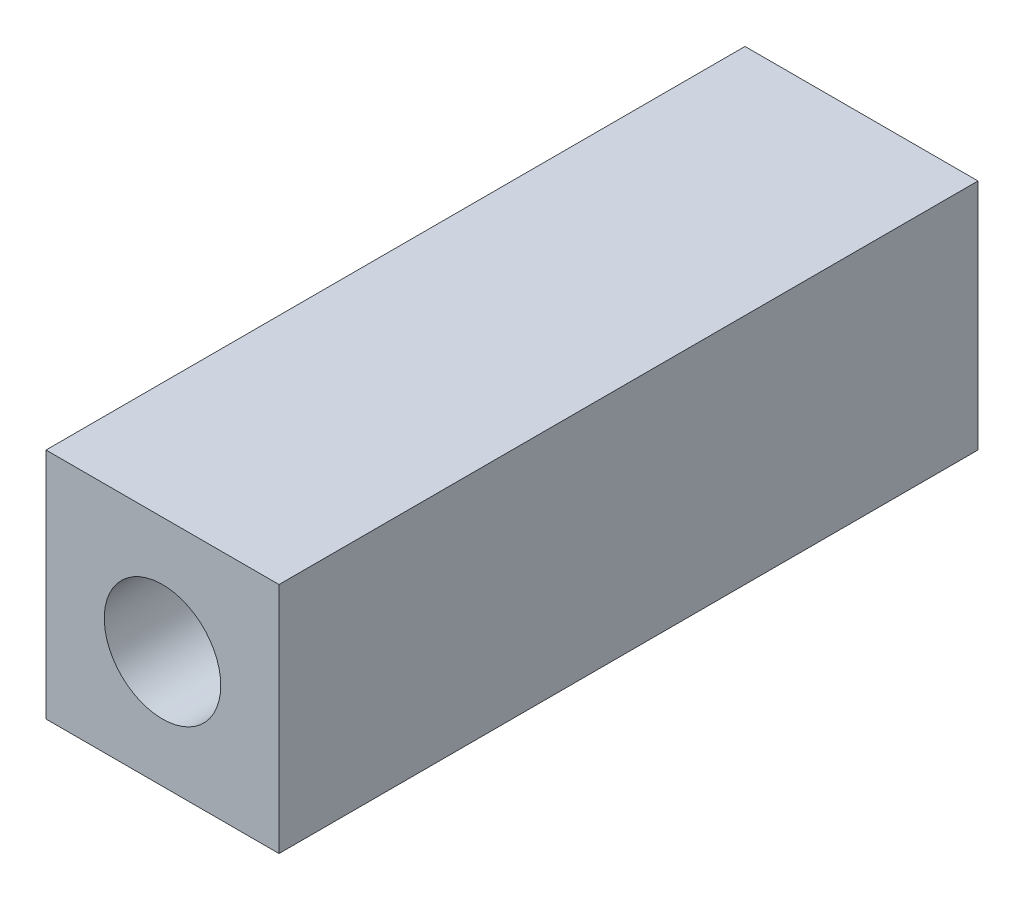
SolidWorks part; units mm, degrees
ref_plane "Plan de face" through (0, 0, 0) normal (0, 0, 1) x (1, 0, 0)
ref_plane "Plan de dessus" through (0, 0, 0) normal (0, 1, 0) x (1, 0, 0)
ref_plane "Plan de droite" through (0, 0, 0) normal (1, 0, 0) x (0, 0, -1)
sketch "Esquisse1" plane through (0, 0, 0) normal (0, 0, 1) x (1, 0, 0)
  line L1 (-5, -5) -> (5, -5)
  line L2 (-5, -5) -> (-5, 5)
  line L3 (-5, 5) -> (5, 5)
  line L4 (5, -5) -> (5, 5)
  line L5 (-5, -5) -> (5, 5) construction
  line L6 (-5, 5) -> (5, -5) construction
  circle A0 centre (0, 0) radius 2.5
  point P0 (0, 0)
  dimension "D3" = 5
  dimension "D1" = 10
  dimension "D2" = 10
extrude "BASE" add sketch "Esquisse1" along normal blind 30
